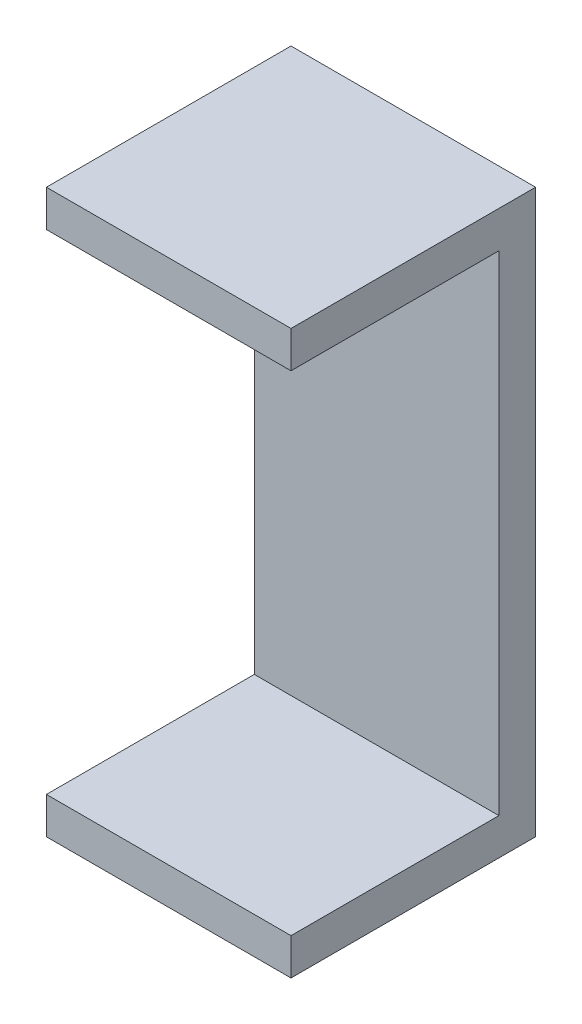
SolidWorks part; units mm, degrees
ref_plane "前视基准面" through (0, 0, 0) normal (0, 0, 1) x (1, 0, 0)
ref_plane "上视基准面" through (0, 0, 0) normal (0, 1, 0) x (1, 0, 0)
ref_plane "右视基准面" through (0, 0, 0) normal (1, 0, 0) x (0, 0, -1)
sketch "草图1" plane through (0, 0, 0) normal (0, 0, 1) x (1, 0, 0)
  line L1 (-10, 20) -> (10, 20)
  line L2 (-10, 20) -> (-10, -20)
  line L3 (-10, -20) -> (10, -20)
  line L4 (10, 20) -> (10, -20)
  line L5 (-10, 20) -> (10, -20) construction
  line L6 (-10, -20) -> (10, 20) construction
  point P0 (0, 0)
  dimension "D1" = 40
  dimension "D2" = 20
extrude "凸台-拉伸1" add sketch "草图1" along normal blind 3
sketch "草图4" plane through (0, 0, 0) normal (0, 0, -1) x (-1, 0, 0)
  line L1 (-10, 20) -> (10, 20)
  line L2 (-10, 20) -> (-10, 23)
  line L3 (-10, 23) -> (10, 23)
  line L4 (10, 20) -> (10, 23)
  line L5 (-10, -20) -> (10, -20)
  line L6 (-10, -20) -> (-10, -23)
  line L7 (-10, -23) -> (10, -23)
  line L8 (10, -20) -> (10, -23)
  dimension "D1" = 3
  dimension "D2" = 3
extrude "凸台-拉伸5" add sketch "草图4" against normal blind 20
